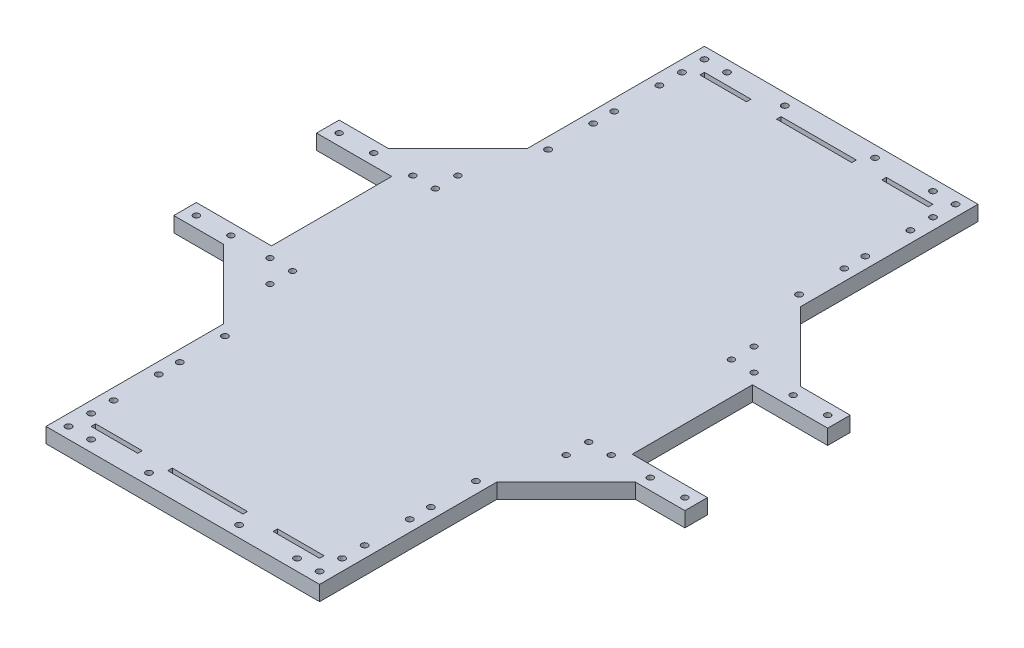
SolidWorks part; units mm, degrees
ref_plane "Front Plane" through (0, 0, 0) normal (0, 0, 1) x (1, 0, 0)
ref_plane "Top Plane" through (0, 0, 0) normal (0, 1, 0) x (1, 0, 0)
ref_plane "Right Plane" through (0, 0, 0) normal (1, 0, 0) x (0, 0, -1)
sketch "Sketch1" plane through (0, 0, 0) normal (0, 1, 0) x (1, 0, 0)
  line L0 (91, 101) -> (137, 55)
  line L1 (-91, -219) -> (91, -219)
  line L2 (-91, -219) -> (-91, 219)
  line L3 (-91, 219) -> (91, 219)
  line L4 (91, -219) -> (91, 219)
  line L5 (-91, -219) -> (91, 219) construction
  line L6 (-91, 219) -> (91, -219) construction
  line L7 (-170, -55) -> (170, -55)
  line L8 (-170, -55) -> (-170, 55)
  line L9 (-170, 55) -> (170, 55)
  line L10 (170, -55) -> (170, 55)
  line L11 (-170, -55) -> (170, 55) construction
  line L12 (-170, 55) -> (170, -55) construction
  line L13 (-91, 101) -> (-137, 55)
  line L14 (-65.62, 0) -> (65.62, 0) construction
  line L15 (91, -101) -> (137, -55)
  line L16 (-91, -101) -> (-137, -55)
  circle A0 centre (0, 0) radius 82.5
  circle A1 centre (0, 0) radius 22.1 construction
  circle A2 centre (0, 0) radius 135 construction
  point P22 (0, 0)
  dimension "D3" = 165
  dimension "D6" = 44.2
  dimension "D7" = 270
  dimension "D1" = 438
  dimension "D2" = 182
  dimension "D4" = 110
  dimension "D5" = 340
  dimension "D8" = 135
  dimension "D9" = 135
  dimension "D10" = 33
  dimension "D11" = 33
extrude "Boss-Extrude1" add sketch "Sketch1" along normal blind 10 contours A0 L9 L4 L3 L2 | L2 L13 L9 | L9 L8 L7 L2 | A0 L7 L2 L1 L4 | A0 L9 L2 L7 | L9 A0 | L7 A0 L9 A1 | L7 A0 | A0 L7 L4 L9 | L7 L10 L9 L4 | L4 L9 L0 | L4 L15 L7 | L16 L2 L7
sketch "Sketch2" plane through (0, 10, 0) normal (0, 1, 0) x (1, 0, 0)
  line L0 (-170, -55) -> (-170, 55) construction
  line L1 (-170, 40) -> (-120, 40)
  line L2 (-170, 40) -> (-170, -40)
  line L3 (-170, -40) -> (-120, -40)
  line L4 (-120, 40) -> (-120, -40)
  line L5 (-170, 40) -> (-120, -40) construction
  line L6 (-170, -40) -> (-120, 40) construction
  line L7 (-145, 0) -> (-145, 55) construction
  line L8 (-170, 55) -> (-137, 55) construction
  line L9 (-145, 0) -> (-145, -55) construction
  line L10 (-170, -55) -> (-137, -55) construction
  line L11 (-153.5, 55) -> (-153.5, 40) construction
  line L12 (-158.7842, 0) -> (-131.2158, 0) construction
  line L13 (-153.5, -40) -> (-153.5, -55) construction
  line L14 (0, -51.1232) -> (0, 51.1232) construction
  line L15 (153.5, -40) -> (153.5, -55) construction
  line L16 (158.7842, 0) -> (131.2158, 0) construction
  line L17 (153.5, 55) -> (153.5, 40) construction
  line L18 (145, 0) -> (145, -55) construction
  line L19 (145, 0) -> (145, 55) construction
  line L20 (170, -40) -> (120, 40) construction
  line L21 (170, 40) -> (120, -40) construction
  line L26 (120, 40) -> (120, -40)
  line L27 (170, -40) -> (120, -40)
  line L28 (170, 40) -> (170, -40)
  line L29 (170, 40) -> (120, 40)
  circle A0 centre (-162.5, 47.5) radius 2
  circle A1 centre (-139.5, 47.5) radius 2
  circle A2 centre (-139.5, -47.5) radius 2
  circle A3 centre (-162.5, -47.5) radius 2
  circle A8 centre (-113.5, 47.5) radius 2
  circle A9 centre (-98.5, 47.5) radius 2
  circle A10 centre (-98.5, 62.5) radius 2
  circle A11 centre (-98.5, -62.5) radius 2
  circle A12 centre (-98.5, -47.5) radius 2
  circle A13 centre (-113.5, -47.5) radius 2
  circle A14 centre (113.5, -47.5) radius 2
  circle A15 centre (98.5, -47.5) radius 2
  circle A16 centre (98.5, -62.5) radius 2
  circle A17 centre (98.5, 62.5) radius 2
  circle A18 centre (98.5, 47.5) radius 2
  circle A19 centre (113.5, 47.5) radius 2
  circle A20 centre (162.5, -47.5) radius 2
  circle A21 centre (139.5, -47.5) radius 2
  circle A22 centre (139.5, 47.5) radius 2
  circle A23 centre (162.5, 47.5) radius 2
  point P4 (-145, 0)
  point P26 (-145, 0)
  point P35 (0, 0)
  point P62 (-113.5, 47.5)
  point P63 (0, 0)
  point P64 (0, 0)
  point P65 (0, 0)
  point P82 (145, 0)
  point P83 (145, 0)
  point P84 (0, 0)
  dimension "D3" = 4
  dimension "D1" = 15
  dimension "D2" = 50
  dimension "D4" = 7.5
  dimension "D5" = 7.5
  dimension "D6" = 23
  dimension "D7" = 15
  dimension "D8" = 26
  dimension "D9" = 15
extrude "Cut-Extrude1" cut sketch "Sketch2" against normal through all
sketch "Sketch3" plane through (0, 10, 0) normal (0, 1, 0) x (1, 0, 0)
  line L0 (-39.7935, 0) -> (39.7935, 0) construction
  line L1 (-91, 219) -> (91, 219) construction
  line L2 (-25, 204) -> (25, 204)
  line L3 (-25, 204) -> (-25, 201)
  line L4 (-25, 201) -> (25, 201)
  line L5 (25, 204) -> (25, 201)
  line L6 (-25, 204) -> (25, 201) construction
  line L7 (-25, 201) -> (25, 204) construction
  line L8 (-60.5, 202.5) -> (0, 202.5) construction
  line L9 (45, 204) -> (76, 204)
  line L10 (45, 204) -> (45, 201)
  line L11 (45, 201) -> (76, 201)
  line L12 (76, 204) -> (76, 201)
  line L13 (45, 204) -> (76, 201) construction
  line L14 (45, 201) -> (76, 204) construction
  line L15 (-45, 204) -> (-76, 204)
  line L16 (-45, 204) -> (-45, 201)
  line L17 (-45, 201) -> (-76, 201)
  line L18 (-76, 204) -> (-76, 201)
  line L19 (-45, 204) -> (-76, 201) construction
  line L20 (-45, 201) -> (-76, 204) construction
  line L21 (0, 202.5) -> (60.5, 202.5) construction
  line L22 (-30, 211.5) -> (30, 211.5) construction
  line L23 (0, 219) -> (0, 204) construction
  line L24 (0, -219) -> (0, -204) construction
  line L25 (-30, -211.5) -> (30, -211.5) construction
  line L26 (0, -202.5) -> (60.5, -202.5) construction
  line L27 (-45, -201) -> (-76, -204) construction
  line L28 (-45, -204) -> (-76, -201) construction
  line L29 (45, -201) -> (76, -204) construction
  line L30 (45, -204) -> (76, -201) construction
  line L31 (-60.5, -202.5) -> (0, -202.5) construction
  line L32 (-25, -201) -> (25, -204) construction
  line L33 (-25, -204) -> (25, -201) construction
  line L34 (-76, -204) -> (-76, -201)
  line L35 (-45, -201) -> (-76, -201)
  line L36 (-45, -204) -> (-45, -201)
  line L37 (-45, -204) -> (-76, -204)
  line L38 (76, -204) -> (76, -201)
  line L39 (45, -201) -> (76, -201)
  line L40 (45, -204) -> (45, -201)
  line L41 (45, -204) -> (76, -204)
  line L42 (25, -204) -> (25, -201)
  line L43 (-25, -201) -> (25, -201)
  line L44 (-25, -204) -> (-25, -201)
  line L45 (-25, -204) -> (25, -204)
  circle A0 centre (-30, 211.5) radius 2.1
  circle A1 centre (30, 211.5) radius 2.1
  circle A2 centre (68.5, 211.5) radius 2.1
  circle A3 centre (83.5, 211.5) radius 2.1
  circle A4 centre (83.5, 196.5) radius 2.1
  circle A5 centre (83.5, 181.5) radius 2.1
  circle A6 centre (83.5, 151.5) radius 2.1
  circle A7 centre (83.5, 137.5) radius 2.1
  circle A8 centre (83.5, 107.5) radius 2.1
  circle A10 centre (-83.5, 107.5) radius 2.1
  circle A11 centre (-83.5, 137.5) radius 2.1
  circle A12 centre (-83.5, 151.5) radius 2.1
  circle A13 centre (-83.5, 181.5) radius 2.1
  circle A14 centre (-83.5, 196.5) radius 2.1
  circle A15 centre (-83.5, 211.5) radius 2.1
  circle A16 centre (-68.5, 211.5) radius 2.1
  circle A17 centre (-68.5, -211.5) radius 2.1
  circle A18 centre (-83.5, -211.5) radius 2.1
  circle A19 centre (-83.5, -196.5) radius 2.1
  circle A20 centre (-83.5, -181.5) radius 2.1
  circle A21 centre (-83.5, -151.5) radius 2.1
  circle A22 centre (-83.5, -137.5) radius 2.1
  circle A23 centre (-83.5, -107.5) radius 2.1
  circle A24 centre (83.5, -107.5) radius 2.1
  circle A25 centre (83.5, -137.5) radius 2.1
  circle A26 centre (83.5, -151.5) radius 2.1
  circle A27 centre (83.5, -181.5) radius 2.1
  circle A28 centre (83.5, -196.5) radius 2.1
  circle A29 centre (83.5, -211.5) radius 2.1
  circle A30 centre (68.5, -211.5) radius 2.1
  circle A31 centre (30, -211.5) radius 2.1
  circle A32 centre (-30, -211.5) radius 2.1
  point P8 (0, 202.5)
  point P12 (0, 219)
  point P18 (60.5, 202.5)
  point P21 (-60.5, 202.5)
  point P24 (0, 211.5)
  point P26 (0, 211.5)
  point P67 (0, 0)
  point P112 (-60.5, -202.5)
  point P113 (60.5, -202.5)
  point P114 (0, -202.5)
  dimension "D2" = 4.2
  dimension "D1" = 60
  dimension "D3" = 50
  dimension "D4" = 3
  dimension "D5" = 15
  dimension "D6" = 31
  dimension "D7" = 60.5
  dimension "D8" = 38.5
  dimension "D9" = 15
  dimension "D10" = 15
  dimension "D11" = 15
  dimension "D12" = 30
  dimension "D13" = 14
  dimension "D14" = 30
extrude "Cut-Extrude2" cut sketch "Sketch3" against normal through all
